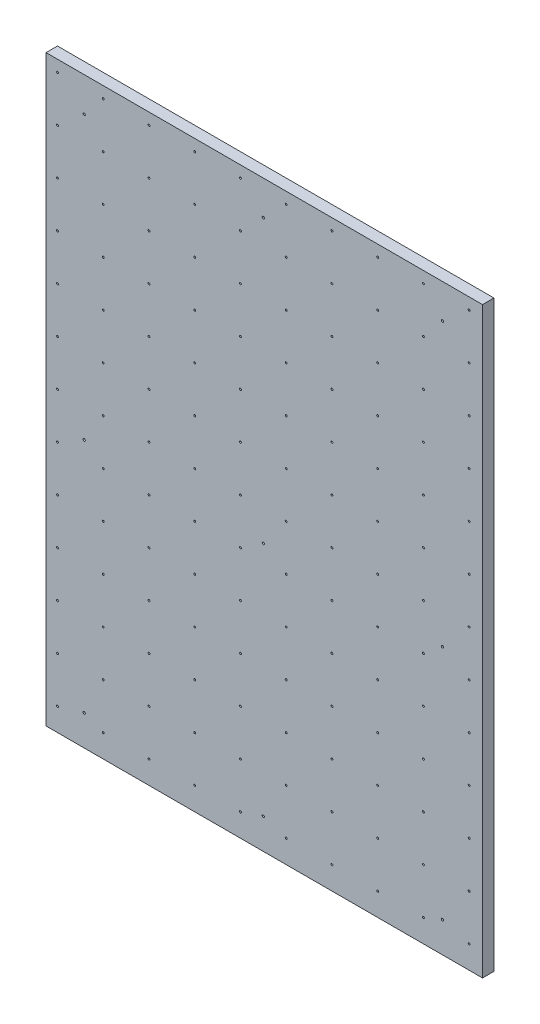
SolidWorks part; units mm, degrees
material "Фанера, берёза, ФСФ ВВ/С ГОСТ 3916.1-96"
ref_plane "Спереди" through (0, 0, 0) normal (0, 0, 1) x (1, 0, 0)
ref_plane "Сверху" through (0, 0, 0) normal (0, 1, 0) x (1, 0, 0)
ref_plane "Справа" through (0, 0, 0) normal (1, 0, 0) x (0, 0, -1)
sketch "Эскиз1" plane through (0, 0, 0) normal (0, 0, 1) x (1, 0, 0)
  line L1 (-572.5, 765) -> (572.5, 765)
  line L2 (-572.5, 765) -> (-572.5, -765)
  line L3 (-572.5, -765) -> (572.5, -765)
  line L4 (572.5, 765) -> (572.5, -765)
  line L5 (0, -765) -> (0, 765) construction
  line L6 (-572.5, 0) -> (572.5, 0) construction
  point P0 (0, 0)
  dimension "D1" = 1145
  dimension "D2" = 1530
extrude "Бобышка-Вытянуть1" add sketch "Эскиз1" along normal mid plane 30
sketch "Эскиз2" plane through (0, 0, 15) normal (0, 0, 1) x (1, 0, 0)
  line L0 (-572.5, 765) -> (-572.5, -765) construction
  line L1 (572.5, 765) -> (-572.5, 765) construction
  line L2 (-542.5, 735) -> (-422.5, 735) construction
  circle A0 centre (-542.5, 735) radius 2.5
  circle A1 centre (-422.5, 735) radius 2.5
  circle A2 centre (-302.5, 735) radius 2.5
  circle A3 centre (-182.5, 735) radius 2.5
  circle A4 centre (-62.5, 735) radius 2.5
  circle A5 centre (57.5, 735) radius 2.5
  circle A6 centre (177.5, 735) radius 2.5
  circle A7 centre (297.5, 735) radius 2.5
  circle A8 centre (417.5, 735) radius 2.5
  circle A9 centre (537.5, 735) radius 2.5
  circle A10 centre (-422.5, 615) radius 2.5
  circle A11 centre (-302.5, 615) radius 2.5
  circle A12 centre (-182.5, 615) radius 2.5
  circle A13 centre (-62.5, 615) radius 2.5
  circle A14 centre (57.5, 615) radius 2.5
  circle A15 centre (177.5, 615) radius 2.5
  circle A16 centre (297.5, 615) radius 2.5
  circle A17 centre (417.5, 615) radius 2.5
  circle A18 centre (537.5, 615) radius 2.5
  circle A19 centre (-422.5, 495) radius 2.5
  circle A20 centre (-302.5, 495) radius 2.5
  circle A21 centre (-182.5, 495) radius 2.5
  circle A22 centre (-62.5, 495) radius 2.5
  circle A23 centre (57.5, 495) radius 2.5
  circle A24 centre (177.5, 495) radius 2.5
  circle A25 centre (297.5, 495) radius 2.5
  circle A26 centre (417.5, 495) radius 2.5
  circle A27 centre (537.5, 495) radius 2.5
  circle A28 centre (-422.5, 375) radius 2.5
  circle A29 centre (-302.5, 375) radius 2.5
  circle A30 centre (-182.5, 375) radius 2.5
  circle A31 centre (-62.5, 375) radius 2.5
  circle A32 centre (57.5, 375) radius 2.5
  circle A33 centre (177.5, 375) radius 2.5
  circle A34 centre (297.5, 375) radius 2.5
  circle A35 centre (417.5, 375) radius 2.5
  circle A36 centre (537.5, 375) radius 2.5
  circle A37 centre (-422.5, 255) radius 2.5
  circle A38 centre (-302.5, 255) radius 2.5
  circle A39 centre (-182.5, 255) radius 2.5
  circle A40 centre (-62.5, 255) radius 2.5
  circle A41 centre (57.5, 255) radius 2.5
  circle A42 centre (177.5, 255) radius 2.5
  circle A43 centre (297.5, 255) radius 2.5
  circle A44 centre (417.5, 255) radius 2.5
  circle A45 centre (537.5, 255) radius 2.5
  circle A46 centre (-422.5, 135) radius 2.5
  circle A47 centre (-302.5, 135) radius 2.5
  circle A48 centre (-182.5, 135) radius 2.5
  circle A49 centre (-62.5, 135) radius 2.5
  circle A50 centre (57.5, 135) radius 2.5
  circle A51 centre (177.5, 135) radius 2.5
  circle A52 centre (297.5, 135) radius 2.5
  circle A53 centre (417.5, 135) radius 2.5
  circle A54 centre (537.5, 135) radius 2.5
  circle A55 centre (-422.5, 15) radius 2.5
  circle A56 centre (-302.5, 15) radius 2.5
  circle A57 centre (-182.5, 15) radius 2.5
  circle A58 centre (-62.5, 15) radius 2.5
  circle A59 centre (57.5, 15) radius 2.5
  circle A60 centre (177.5, 15) radius 2.5
  circle A61 centre (297.5, 15) radius 2.5
  circle A62 centre (417.5, 15) radius 2.5
  circle A63 centre (537.5, 15) radius 2.5
  circle A64 centre (-422.5, -105) radius 2.5
  circle A65 centre (-302.5, -105) radius 2.5
  circle A66 centre (-182.5, -105) radius 2.5
  circle A67 centre (-62.5, -105) radius 2.5
  circle A68 centre (57.5, -105) radius 2.5
  circle A69 centre (177.5, -105) radius 2.5
  circle A70 centre (297.5, -105) radius 2.5
  circle A71 centre (417.5, -105) radius 2.5
  circle A72 centre (537.5, -105) radius 2.5
  circle A73 centre (-422.5, -225) radius 2.5
  circle A74 centre (-302.5, -225) radius 2.5
  circle A75 centre (-182.5, -225) radius 2.5
  circle A76 centre (-62.5, -225) radius 2.5
  circle A77 centre (57.5, -225) radius 2.5
  circle A78 centre (177.5, -225) radius 2.5
  circle A79 centre (297.5, -225) radius 2.5
  circle A80 centre (417.5, -225) radius 2.5
  circle A81 centre (537.5, -225) radius 2.5
  circle A82 centre (-422.5, -345) radius 2.5
  circle A83 centre (-302.5, -345) radius 2.5
  circle A84 centre (-182.5, -345) radius 2.5
  circle A85 centre (-62.5, -345) radius 2.5
  circle A86 centre (57.5, -345) radius 2.5
  circle A87 centre (177.5, -345) radius 2.5
  circle A88 centre (297.5, -345) radius 2.5
  circle A89 centre (417.5, -345) radius 2.5
  circle A90 centre (537.5, -345) radius 2.5
  circle A91 centre (-422.5, -465) radius 2.5
  circle A92 centre (-302.5, -465) radius 2.5
  circle A93 centre (-182.5, -465) radius 2.5
  circle A94 centre (-62.5, -465) radius 2.5
  circle A95 centre (57.5, -465) radius 2.5
  circle A96 centre (177.5, -465) radius 2.5
  circle A97 centre (297.5, -465) radius 2.5
  circle A98 centre (417.5, -465) radius 2.5
  circle A99 centre (537.5, -465) radius 2.5
  circle A100 centre (-422.5, -585) radius 2.5
  circle A101 centre (-302.5, -585) radius 2.5
  circle A102 centre (-182.5, -585) radius 2.5
  circle A103 centre (-62.5, -585) radius 2.5
  circle A104 centre (57.5, -585) radius 2.5
  circle A105 centre (177.5, -585) radius 2.5
  circle A106 centre (297.5, -585) radius 2.5
  circle A107 centre (417.5, -585) radius 2.5
  circle A108 centre (537.5, -585) radius 2.5
  circle A109 centre (-422.5, -705) radius 2.5
  circle A110 centre (-302.5, -705) radius 2.5
  circle A111 centre (-182.5, -705) radius 2.5
  circle A112 centre (-62.5, -705) radius 2.5
  circle A113 centre (57.5, -705) radius 2.5
  circle A114 centre (177.5, -705) radius 2.5
  circle A115 centre (297.5, -705) radius 2.5
  circle A116 centre (417.5, -705) radius 2.5
  circle A117 centre (537.5, -705) radius 2.5
  circle A118 centre (-542.5, 615) radius 2.5
  circle A119 centre (-542.5, 495) radius 2.5
  circle A120 centre (-542.5, 375) radius 2.5
  circle A121 centre (-542.5, 255) radius 2.5
  circle A122 centre (-542.5, 135) radius 2.5
  circle A123 centre (-542.5, 15) radius 2.5
  circle A124 centre (-542.5, -105) radius 2.5
  circle A125 centre (-542.5, -225) radius 2.5
  circle A126 centre (-542.5, -345) radius 2.5
  circle A127 centre (-542.5, -465) radius 2.5
  circle A128 centre (-542.5, -585) radius 2.5
  circle A129 centre (-542.5, -705) radius 2.5
  dimension "D1" = 5
  dimension "D2" = 30
  dimension "D3" = 30
  dimension "D6" = 120
  dimension "D4" = 10
  dimension "D5" = 13
extrude "Вырез-Вытянуть1" cut sketch "Эскиз2" against normal through all
sketch "Эскиз3" plane through (0, 0, 15) normal (0, 0, 1) x (1, 0, 0)
  circle A0 centre (467.5, -685) radius 3 construction
  circle A1 centre (-2.5, -685) radius 3 construction
  circle A2 centre (-472.5, -685) radius 3 construction
  circle A3 centre (-472.5, -65) radius 3 construction
  circle A4 centre (-2.5, -65) radius 3 construction
  circle A5 centre (467.5, -65) radius 3 construction
  circle A6 centre (467.5, 675) radius 3 construction
  circle A7 centre (-2.5, 675) radius 3 construction
  circle A8 centre (-472.5, 675) radius 3 construction
  circle A9 centre (467.5, -685) radius 3
  circle A10 centre (-2.5, -685) radius 3
  circle A11 centre (-472.5, -685) radius 3
  circle A12 centre (-472.5, -65) radius 3
  circle A13 centre (-2.5, -65) radius 3
  circle A14 centre (467.5, -65) radius 3
  circle A15 centre (467.5, 675) radius 3
  circle A16 centre (-2.5, 675) radius 3
  circle A17 centre (-472.5, 675) radius 3
extrude "Вырез-Вытянуть2" cut sketch "Эскиз3" against normal through all
equation "\"ширина 1-я панель\"=1145"
equation "\"толщина дсп\"=30"
equation "\"D1@Эскиз1\"=\"ширина 1-я панель\""
equation "\"D3@Эскиз2\"=\"D2@Эскиз2\""
equation "\"длина панелей\"=1530"
equation "\"ширина 2-я панель\"=1070"
equation "\"D2@Эскиз1\"=\"длина панелей\""
